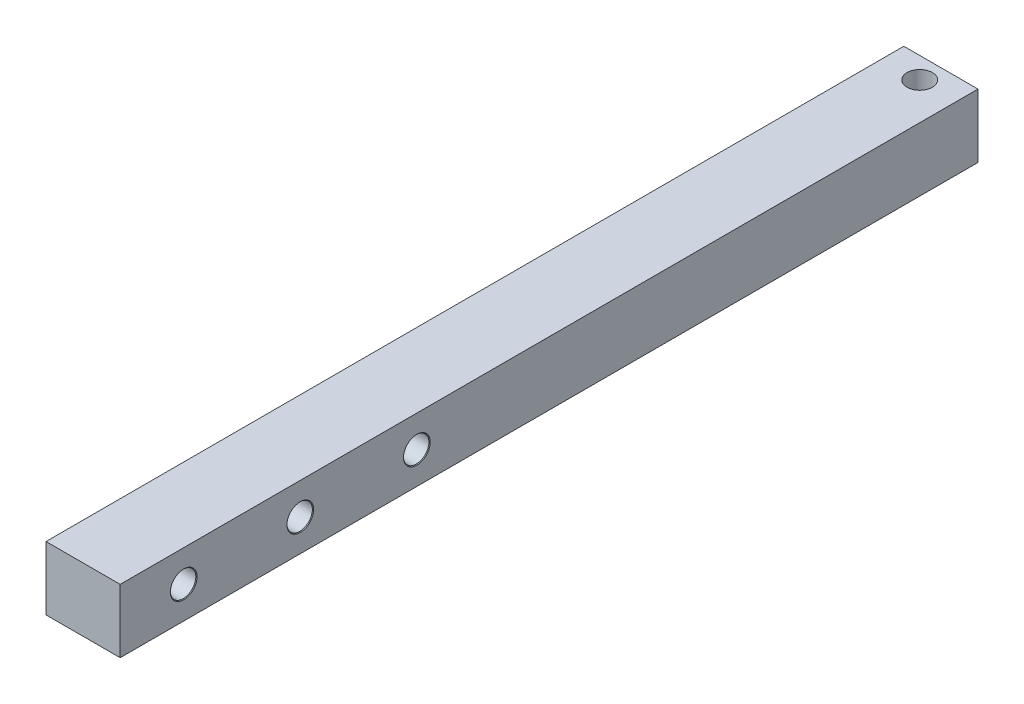
SolidWorks part; units mm, degrees
ref_plane "Front Plane" through (0, 0, 0) normal (0, 0, 1) x (1, 0, 0)
ref_plane "Top Plane" through (0, 0, 0) normal (0, 1, 0) x (1, 0, 0)
ref_plane "Right Plane" through (0, 0, 0) normal (1, 0, 0) x (0, 0, -1)
sketch "Sketch1" plane through (0, 0, 0) normal (0, 0, 1) x (1, 0, 0)
  line L1 (-2.7797, -14.329) -> (32.2203, -14.329)
  line L2 (-2.7797, -14.329) -> (-2.7797, -44.329)
  line L3 (-2.7797, -44.329) -> (32.2203, -44.329)
  line L4 (32.2203, -14.329) -> (32.2203, -44.329)
  dimension "D1" = 30
  dimension "D2" = 35
extrude "Boss-Extrude1" add sketch "Sketch1" along normal mid plane 404.8
sketch "Sketch4" plane through (-2.7797, 0, 0) normal (-1, 0, 0) x (0, 0, 1)
  line L0 (202.4, -14.329) -> (202.4, -44.329) construction
  line L1 (202.4, -14.329) -> (-202.4, -14.329) construction
  line L4 (202.4, -44.329) -> (-202.4, -44.329) construction
  circle A0 centre (172.4, -29.329) radius 6
  circle A1 centre (62.4, -29.329) radius 6
  circle A2 centre (117.4, -29.329) radius 6
  point P8 (202.4, -29.329)
  dimension "D5" = 12
  dimension "D6" = 12
  dimension "D7" = 12
  dimension "D1" = 55
  dimension "D2" = 30
  dimension "D3" = 55
  dimension "D4" = 110
  dimension "D8" = 15
  dimension "D9" = 15
  dimension "D10" = 15
  dimension "D11" = 15
extrude "Cut-Extrude1" cut sketch "Sketch4" against normal through all
sketch "Sketch5" plane through (0, -14.329, 0) normal (0, 1, 0) x (1, 0, 0)
  line L1 (-2.7797, -202.4) -> (-2.7797, 202.4) construction
  line L2 (32.2203, 202.4) -> (-2.7797, 202.4) construction
  circle A0 centre (14.7203, 192.4) radius 6
  dimension "D1" = 12
  dimension "D2" = 17.5
  dimension "D3" = 10
extrude "Cut-Extrude2" cut sketch "Sketch5" against normal through all
chamfer "Chamfer1" distance 0.3 angle 45 6 edges at (32.2203, -35.329, 62.4) (32.2203, -35.329, 117.4) (32.2203, -35.329, 172.4) (-2.7797, -35.329, 172.4) (-2.7797, -35.329, 62.4) (-2.7797, -35.329, 117.4)
